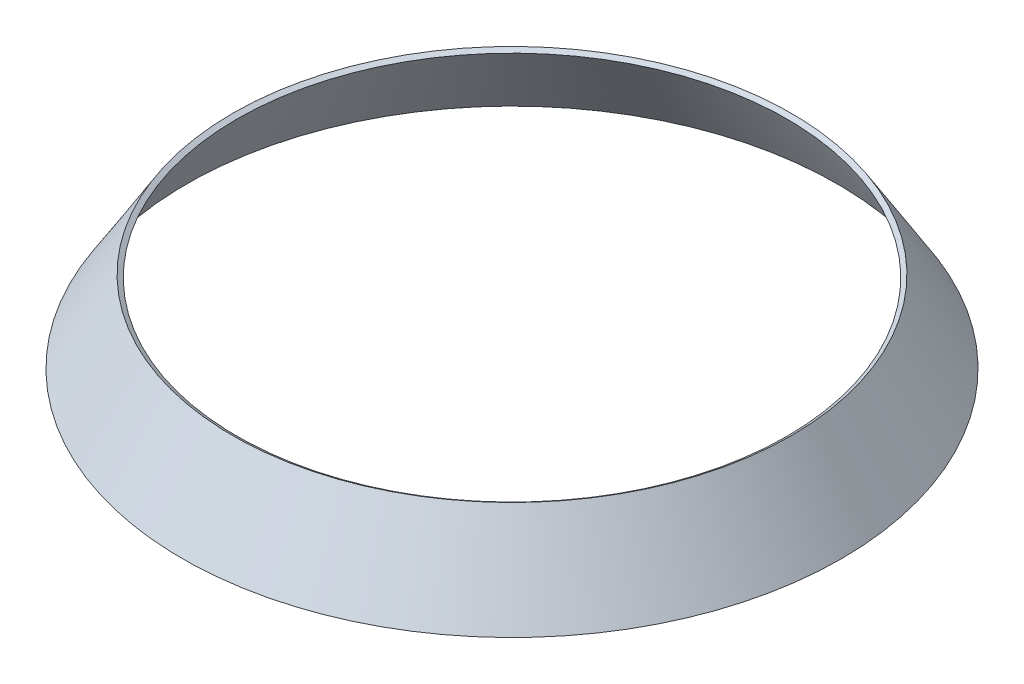
SolidWorks part; units mm, degrees
ref_plane "Front Plane" through (0, 0, 0) normal (0, 0, 1) x (1, 0, 0)
ref_plane "Top Plane" through (0, 0, 0) normal (0, 1, 0) x (1, 0, 0)
ref_plane "Right Plane" through (0, 0, 0) normal (1, 0, 0) x (0, 0, -1)
sketch "Sketch1" plane through (0, 0, 0) normal (0, 0, 1) x (1, 0, 0)
  line L0 (0, -1106.9178) -> (0, 54238.9737) construction
  line L1 (37.9489, 5.7142) -> (44.78, -5.3464)
  line L2 (37.9489, 5.7142) -> (37.3533, 5.3464)
  line L3 (44.78, -5.3464) -> (44.1844, -5.7142)
  line L4 (37.3533, 5.3464) -> (44.1844, -5.7142)
  line L5 (37.9489, 5.7142) -> (44.1844, -5.7142) construction
  line L6 (44.78, -5.3464) -> (37.3533, 5.3464) construction
  point P4 (41.0667, 0)
  dimension "D1" = 31.7
  dimension "D2" = 0.7
  dimension "D3" = 44.78
  dimension "D4" = 13
revolve "Revolve1" add sketch "Sketch1" angle 360 about L0
